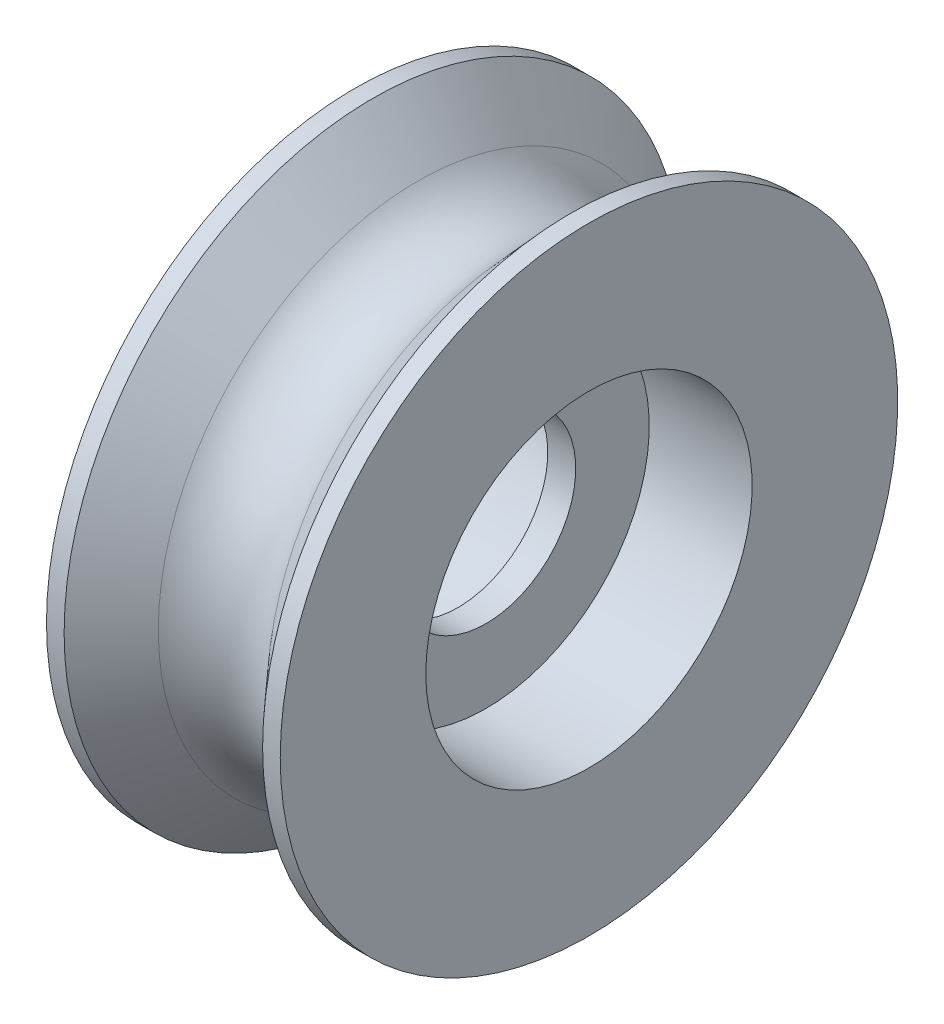
SolidWorks part; units mm, degrees
ref_plane "Front Plane" through (0, 0, 0) normal (0, 0, 1) x (1, 0, 0)
ref_plane "Top Plane" through (0, 0, 0) normal (0, 1, 0) x (1, 0, 0)
ref_plane "Right Plane" through (0, 0, 0) normal (1, 0, 0) x (0, 0, -1)
sketch "Sketch1" plane through (0, 0, 0) normal (0, 1, 0) x (1, 0, 0)
  line L0 (-7.95, 11.1) -> (-0.95, 11.1)
  line L1 (-3.7158, 0) -> (4, 0) construction
  line L2 (-0.95, 11.1) -> (-0.95, 6.1)
  line L3 (-0.95, 6.1) -> (0.95, 6.1)
  line L4 (0.95, 6.1) -> (0.95, 11.1)
  line L5 (6.75, 21) -> (7.95, 21)
  line L6 (7.95, 21) -> (7.95, 11.1)
  line L7 (-6.75, 21) -> (-7.95, 21)
  line L8 (-7.95, 21) -> (-7.95, 11.1)
  line L9 (0.95, 11.1) -> (7.95, 11.1)
  line L10 (6.75, 21) -> (3.7037, 17.641)
  line L11 (-6.75, 21) -> (-3.7037, 17.641)
  arc A0 (-3.7037, 17.641) -> (3.7037, 17.641) centre (0, 21) ccw
  point P1 (0, 16)
  dimension "D1" = 10
  dimension "D3" = 5
  dimension "D2" = 11.1
  dimension "D4" = 1.9
  dimension "D5" = 7
  dimension "D6" = 7
  dimension "D7" = 0.95
  dimension "D8" = 16
  dimension "D9" = 90
  dimension "D10" = 90
  dimension "D11" = 1.2
  dimension "D12" = 1.2
revolve "Revolve1" add sketch "Sketch1" angle 360 about L1
